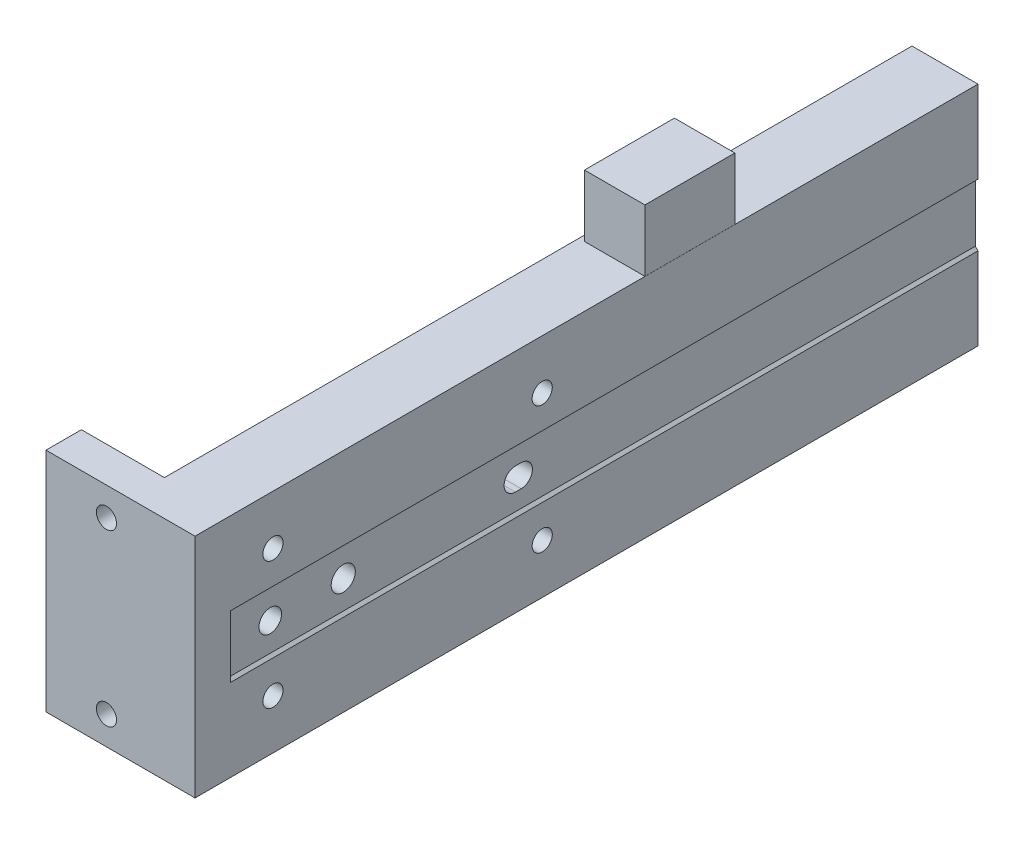
SolidWorks part; units mm, degrees
ref_plane "Front" through (0, 0, 0) normal (0, 0, 1) x (1, 0, 0)
ref_plane "Top" through (0, 0, 0) normal (0, 1, 0) x (1, 0, 0)
ref_plane "Right" through (0, 0, 0) normal (1, 0, 0) x (0, 0, -1)
sketch "Sketch1" plane through (0, 0, -942.5686) normal (0, 0, 1) x (1, 0, 0)
  line L0 (6.2103, 16) -> (-6.2103, 16) construction
  line L1 (-5.1213, 16) -> (15.9087, 16)
  line L2 (-5.1213, 16) -> (-5.1213, -16)
  line L3 (-5.1213, -16) -> (15.9087, -16)
  line L4 (15.9087, 16) -> (15.9087, 4.38)
  line L5 (-5.1213, 0) -> (15.5287, 0) construction
  line L6 (-6.5913, 15.619) -> (-6.5913, 7.881) construction
  line L8 (-1.4097, -16) -> (1.4097, -16) construction
  line L9 (15.5287, 4) -> (15.5287, -4)
  line L10 (15.5287, -4) -> (15.9087, -4.38)
  line L11 (15.5287, 4) -> (15.9087, 4.38)
  line L12 (15.9087, -4.38) -> (15.9087, -16)
  dimension "D1" = 1.47
  dimension "D2" = 22.5
  dimension "D3" = 45
  dimension "D4" = 0.38
  dimension "D5" = 8
extrude "Base-Extrude" add sketch "Sketch1" along normal up to surface (5 mm away)
sketch "Sketch3" plane through (0, 0, -942.5686) normal (0, 0, -1) x (-1, 0, 0)
  line L0 (-15.9087, 4.38) -> (-15.9087, 16) construction
  line L1 (-15.9087, 16) -> (5.1213, 16) construction
  line L2 (-15.9087, 4.38) -> (-15.9087, 16)
  line L3 (-15.9087, 16) -> (-6.5913, 16)
  line L4 (5.1213, -16) -> (-15.9087, -16) construction
  line L5 (-15.9087, -16) -> (-15.9087, -4.38) construction
  line L6 (-15.9087, -4.38) -> (-15.5287, -4) construction
  line L7 (-15.5287, -4) -> (-15.5287, 4) construction
  line L8 (-15.5287, 4) -> (-15.9087, 4.38) construction
  line L9 (-6.5913, -16) -> (-15.9087, -16)
  line L10 (-15.9087, -16) -> (-15.9087, -4.38)
  line L11 (-15.9087, -4.38) -> (-15.5287, -4)
  line L12 (-15.5287, -4) -> (-15.5287, 4)
  line L13 (-15.5287, 4) -> (-15.9087, 4.38)
  line L14 (-6.5913, -7.881) -> (-6.5913, -15.619) construction
  line L19 (-6.5913, 16) -> (-6.5913, -16)
extrude "Boss-Extrude1" add sketch "Sketch3" along normal up to surface (105.5 mm away)
sketch "Sketch15" plane through (0, 0, -937.5686) normal (0, 0, 1) x (1, 0, 0)
  line L0 (15.9087, -4.38) -> (15.5287, -4) construction
  line L1 (15.5287, -4) -> (15.5287, 4) construction
  line L2 (15.5287, 4) -> (15.9087, 4.38) construction
  line L3 (15.9087, -4.38) -> (15.5287, -4)
  line L4 (15.5287, -4) -> (15.5287, 4)
  line L5 (15.5287, 4) -> (15.9087, 4.38)
  line L6 (15.9087, -4.38) -> (15.9087, 4.38)
extrude "Boss-Extrude3" add sketch "Sketch15" against normal up to surface (5 mm away) up to face at (0.735, -4, -942.5686)
hole_wizard "3.4 Diameter Hole1" positions "Sketch5" profile "Sketch4" hole size "M3.4" standard "Ansi Metric" end condition through all
sketch "Sketch5" plane through (15.5287, 0, 0) normal (1, 0, 0) x (0, 0, -1)
  point P0 (958.8686, 0)
sketch "Sketch4" plane through (15.5287, 0, -958.8686) normal (0, 1, 0) x (0, 0, -1)
  line L0 (0, 0) -> (0, 20.65)
  line L1 (0, 20.65) -> (1.7, 20.65)
  line L2 (1.7, 20.65) -> (1.7, 0)
  line L5 (1.7, 0) -> (0, 0)
  line L11 (0, -6.35) -> (0, 107.95) construction
  dimension "Thru Hole Dia." = 3.4
  dimension "Thru Hole Depth" = 20.65
hole_wizard "#4-40 Tapped Hole1" positions "Sketch7" profile "Sketch6" tap size "#4-40" standard "Ansi Inch"
sketch "Sketch7" plane through (15.9087, 0, 0) normal (1, 0, 0) x (0, 0, -1)
  point P0 (948.5686, 9)
  point P1 (986.5686, 9)
  point P3 (948.5686, -9)
  point P4 (986.5686, -9)
sketch "Sketch6" plane through (15.9087, 9, -948.5686) normal (0, 1, 0) x (0, 0, -1)
  line L0 (0, 0) -> (0, 7.9182)
  line L1 (0, 7.9182) -> (1.1303, 7.239)
  line L2 (1.1303, 7.239) -> (1.1303, 4.064)
  line L3 (1.1303, 4.064) -> (1.4224, 4.064)
  line L4 (1.4224, 4.064) -> (1.4224, 0)
  line L5 (1.4224, 0) -> (0, 0)
  line L10 (0, 7.9182) -> (-1.1303, 7.239) construction
  line L11 (0, -6.35) -> (0, 107.95) construction
  dimension "Tap Drill Dia." = 2.2606
  dimension "Tap Drill Depth" = 7.239
  dimension "Thread Dia." = 2.8448
  dimension "Thread Depth" = 4.064
  dimension "Drill Angle" = 118
hole_wizard "#4-40 Tapped Hole2" positions "Sketch10" profile "Sketch9" tap size "#4-40" standard "Ansi Inch" end condition through all
sketch "Sketch10" plane through (0, 0, -937.5686) normal (0, 0, 1) x (1, 0, 0)
  line L0 (-6.5913, 15.619) -> (-6.5913, 7.881) construction
  line L1 (-6.2103, 0) -> (3.4087, 0) construction
  line L2 (-6.2103, 7.5) -> (-6.2103, -7.5) construction
  point P0 (3.4087, 12)
  point P1 (3.4087, -12)
  dimension "D1" = 10
  dimension "D2" = 24
sketch "Sketch9" plane through (3.4087, 12, -937.5686) normal (1, 0, 0) x (0, -1, 0)
  line L0 (0, 0) -> (0, 110.5)
  line L1 (0, 110.5) -> (1.1303, 110.5)
  line L3 (1.1303, 110.5) -> (1.1303, 5.6896)
  line L4 (1.1303, 5.6896) -> (1.4224, 5.6896)
  line L5 (1.4224, 5.6896) -> (1.4224, 0)
  line L7 (1.4224, 0) -> (0, 0)
  line L11 (0, -6.35) -> (0, 107.95) construction
  dimension "Thru Tap Drill Dia." = 2.2606
  dimension "Thru Tap Drill Depth" = 110.5
  dimension "Thread Dia." = 2.8448
  dimension "Thread Depth" = 5.6896
sketch "Sketch11" plane through (15.5287, 0, 0) normal (1, 0, 0) x (0, 0, -1)
  line L0 (983.5686, 9) -> (983.5686, 0) construction
  line L2 (937.5686, 0) -> (1048.0686, 0) construction
  line L4 (985.5686, 0) -> (985.5686, 9) construction
  line L5 (981.5686, 0) -> (981.5686, 9) construction
  line L6 (983.1625, 1.5939) -> (983.9748, 1.5939)
  line L7 (983.1625, -1.5938) -> (983.9748, -1.5938)
  arc A0 (983.9748, -1.5938) -> (983.9748, 1.5939) centre (983.9748, 0) ccw
  arc A1 (983.1625, 1.5939) -> (983.1625, -1.5938) centre (983.1625, 0) ccw
  dimension "D1" = 3.1877
  dimension "D2" = 4
extrude "Cut-Extrude1" cut sketch "Sketch11" against normal blind 3.5
hole_wizard "Hole1" positions "Sketch13" profile "Sketch12" legacy
sketch "Sketch13" plane through (15.5287, 0, 0) normal (1, 0, 0) x (0, 0, -1)
  line L0 (937.5686, 0) -> (1048.0686, 0) construction
  point P0 (948.5686, 0)
sketch "Sketch12" plane through (15.5287, 0, -948.5686) normal (0, 1, 0) x (0, 0, -1)
  line L0 (0, 0) -> (0, 2.54)
  line L1 (0, 2.54) -> (1.5939, 2.54)
  line L2 (1.5939, 2.54) -> (1.5939, 0)
  line L3 (1.5939, 0) -> (0, 0)
  line L4 (0, 110) -> (0, -10) construction
  dimension "Diameter" = 3.1877
  dimension "Depth" = 2.54
sketch "Sketch2" plane through (0, 0, -937.5686) normal (0, 0, 1) x (1, 0, 0)
  line L0 (15.9087, -16) -> (15.9087, 16) construction
  circle A2 centre (0, 7) radius 2.15
  circle A3 centre (0, -7) radius 2.15
  circle A4 centre (11.4087, 12) radius 3.175
  circle A5 centre (11.4087, -12) radius 3.175
  dimension "D1" = 6.35
  dimension "D4" = 4.3
  dimension "D3" = 4.5
sketch "Sketch14" plane through (0, 16, 0) normal (0, 1, 0) x (-1, 0, 0)
  line L1 (-15.8987, -1001.0686) -> (-7.3687, -1001.0686)
  line L2 (-15.8987, -1001.0686) -> (-15.8987, -1013.7686)
  line L3 (-15.8987, -1013.7686) -> (-7.3687, -1013.7686)
  line L4 (-7.3687, -1001.0686) -> (-7.3687, -1013.7686)
  line L5 (-15.9087, -937.5686) -> (-15.9087, -1048.0686) construction
  line L7 (-8.925, -1001.0686) -> (8.925, -1001.0686) construction
  dimension "D1" = 12.7
  dimension "D2" = 8.53
  dimension "D3" = 0.01
extrude "Boss-Extrude2" add sketch "Sketch14" along normal blind 8.73
chamfer "Chamfer1" [suppressed] distance 1 angle 45
